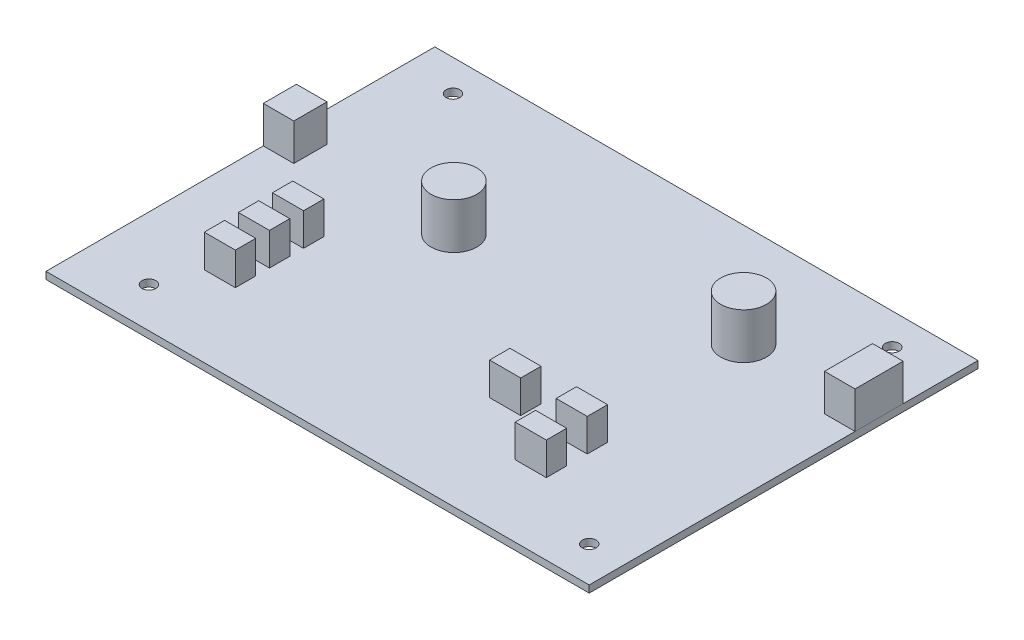
SolidWorks part; units mm, degrees
ref_plane "Front Plane" through (0, 0, 0) normal (0, 0, 1) x (1, 0, 0)
ref_plane "Top Plane" through (0, 0, 0) normal (0, 1, 0) x (1, 0, 0)
ref_plane "Right Plane" through (0, 0, 0) normal (1, 0, 0) x (0, 0, -1)
sketch "Sketch1" plane through (0, 0, 0) normal (0, 1, 0) x (1, 0, 0)
  line L0 (0, -55) -> (0, 55) construction
  line L1 (-60.325, 43.18) -> (60.325, 43.18)
  line L2 (-60.325, 43.18) -> (-60.325, -43.18)
  line L3 (-60.325, -43.18) -> (60.325, -43.18)
  line L4 (60.325, 43.18) -> (60.325, -43.18)
  line L5 (-55, 0) -> (55, 0) construction
  point P4 (0, 43.18)
  point P7 (-60.325, 0)
  dimension "D1" = 120.65
  dimension "D2" = 86.36
extrude "PCB" add sketch "Sketch1" along normal blind 1.5748
sketch "Sketch2" plane through (0, 1.5748, 0) normal (0, 1, 0) x (1, 0, 0)
  line L0 (-60.325, -43.18) -> (60.325, -43.18) construction
  line L1 (-60.325, 43.18) -> (-60.325, -43.18) construction
  line L2 (60.325, -43.18) -> (60.325, 43.18) construction
  circle A0 centre (-22.225, 9.3218) radius 5.08
  circle A1 centre (31.115, 20.32) radius 5.08
  dimension "D1" = 10.16
  dimension "D2" = 52.5018
  dimension "D3" = 63.5
  dimension "D4" = 38.1
  dimension "D5" = 29.21
extrude "Capacitors" add sketch "Sketch2" along normal blind 10.16
sketch "Sketch3" plane through (0, 1.5748, 0) normal (0, 1, 0) x (1, 0, 0)
  line L0 (-60.325, 43.18) -> (-60.325, -43.18) construction
  line L1 (-60.325, 12.446) -> (-53.5432, 12.446)
  line L2 (-60.325, 12.446) -> (-60.325, 5.08)
  line L3 (-60.325, 5.08) -> (-53.5432, 5.08)
  line L4 (-53.5432, 12.446) -> (-53.5432, 5.08)
  line L5 (60.325, -43.18) -> (60.325, 43.18) construction
  line L6 (60.325, 26.543) -> (53.5432, 26.543)
  line L7 (60.325, 26.543) -> (60.325, 15.875)
  line L8 (60.325, 15.875) -> (53.5432, 15.875)
  line L9 (53.5432, 26.543) -> (53.5432, 15.875)
  line L10 (-60.325, -43.18) -> (60.325, -43.18) construction
  dimension "D1" = 7.366
  dimension "D2" = 6.7818
  dimension "D3" = 48.26
  dimension "D4" = 59.055
  dimension "D5" = 10.668
extrude "Connectors" add sketch "Sketch3" along normal blind 8.1788 separate body
sketch "Sketch4" plane through (0, 1.5748, 0) normal (0, 1, 0) x (1, 0, 0)
  line L0 (-60.325, -43.18) -> (60.325, -43.18) construction
  line L1 (-43.053, -5.6388) -> (-36.1442, -5.6388)
  line L2 (-43.053, -5.6388) -> (-43.053, -10.16)
  line L3 (-43.053, -10.16) -> (-36.1442, -10.16)
  line L4 (-36.1442, -5.6388) -> (-36.1442, -10.16)
  line L5 (-43.053, -13.208) -> (-36.1442, -13.208)
  line L6 (-43.053, -13.208) -> (-43.053, -17.7292)
  line L7 (-43.053, -17.7292) -> (-36.1442, -17.7292)
  line L8 (-36.1442, -13.208) -> (-36.1442, -17.7292)
  line L9 (-43.053, -20.7772) -> (-36.1442, -20.7772)
  line L10 (-43.053, -20.7772) -> (-43.053, -25.2984)
  line L11 (-43.053, -25.2984) -> (-36.1442, -25.2984)
  line L12 (-36.1442, -20.7772) -> (-36.1442, -25.2984)
  line L13 (28.0162, -13.6906) -> (34.925, -13.6906)
  line L14 (28.0162, -13.6906) -> (28.0162, -18.2118)
  line L15 (28.0162, -18.2118) -> (34.925, -18.2118)
  line L16 (34.925, -13.6906) -> (34.925, -18.2118)
  line L17 (28.0162, -22.7838) -> (34.925, -22.7838)
  line L18 (28.0162, -22.7838) -> (28.0162, -27.305)
  line L19 (28.0162, -27.305) -> (34.925, -27.305)
  line L20 (34.925, -22.7838) -> (34.925, -27.305)
  line L21 (13.2334, -13.6906) -> (20.1422, -13.6906)
  line L22 (13.2334, -13.6906) -> (13.2334, -18.2118)
  line L23 (13.2334, -18.2118) -> (20.1422, -18.2118)
  line L24 (20.1422, -13.6906) -> (20.1422, -18.2118)
  line L25 (-60.325, 43.18) -> (-60.325, -43.18) construction
  line L26 (60.325, -43.18) -> (60.325, 43.18) construction
  dimension "D1" = 4.5212
  dimension "D2" = 6.9088
  dimension "D3" = 33.02
  dimension "D4" = 3.048
  dimension "D5" = 3.048
  dimension "D6" = 17.272
  dimension "D7" = 4.572
  dimension "D8" = 7.874
  dimension "D9" = 25.4
  dimension "D10" = 15.875
extrude "Pots" add sketch "Sketch4" along normal blind 7.239 separate body
sketch "Sketch5" plane through (0, 1.5748, 0) normal (0, 1, 0) x (1, 0, 0)
  line L0 (-60.325, 43.18) -> (-60.325, -43.18) construction
  line L1 (-60.325, -43.18) -> (60.325, -43.18) construction
  line L2 (60.325, -43.18) -> (60.325, 43.18) construction
  line L3 (60.325, 43.18) -> (-60.325, 43.18) construction
  circle A0 centre (-49.3014, 36.195) radius 1.524
  circle A1 centre (48.26, 36.195) radius 1.524
  circle A2 centre (-46.355, -34.29) radius 1.524
  circle A3 centre (52.451, -35.306) radius 1.524
  dimension "D1" = 13.97
  dimension "D2" = 3.048
  dimension "D3" = 8.89
  dimension "D4" = 11.0236
  dimension "D5" = 12.065
  dimension "D6" = 7.874
  dimension "D7" = 7.874
  dimension "D8" = 6.985
  dimension "D9" = 6.985
extrude "Cut-Extrude1" cut sketch "Sketch5" against normal through all
